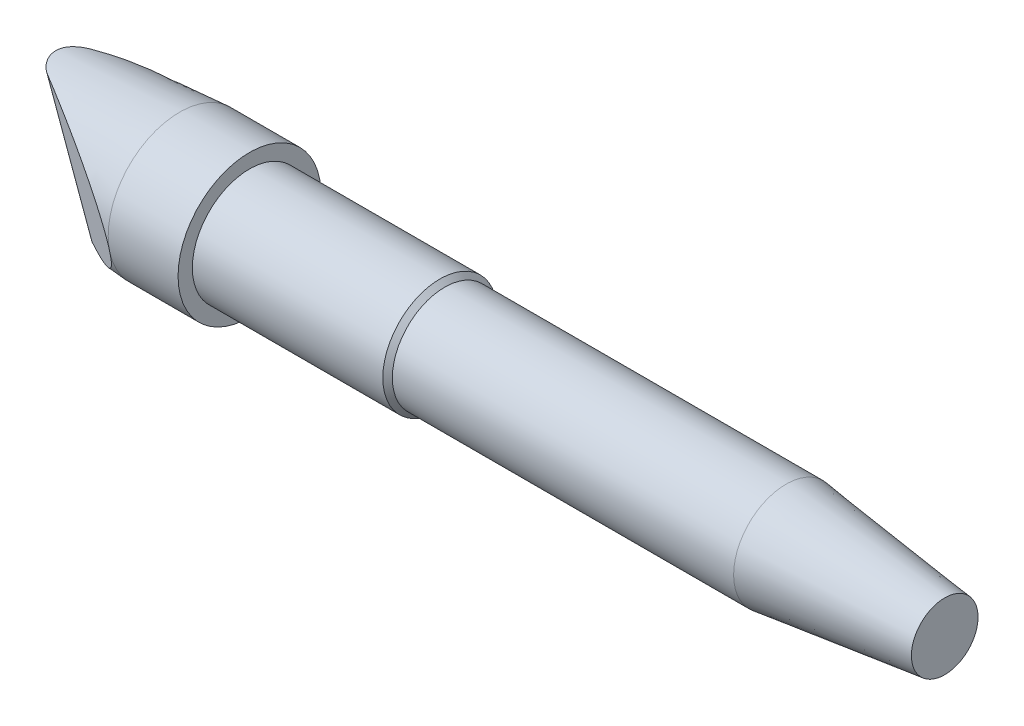
SolidWorks part; units mm, degrees
ref_plane "Plano frontal" through (0, 0, 0) normal (0, 0, 1) x (1, 0, 0)
ref_plane "Plano superior" through (0, 0, 0) normal (0, 1, 0) x (1, 0, 0)
ref_plane "Plano direito" through (0, 0, 0) normal (1, 0, 0) x (0, 0, -1)
sketch "Esboço1" plane through (0, 0, 0) normal (0, 0, 1) x (1, 0, 0)
  line L0 (0, 0) -> (29.4388, 0) construction
  line L1 (6.2, 2.25) -> (6.2, 1.8)
  line L2 (6.2, 2.25) -> (4.7, 2.25)
  line L3 (0, 2.25) -> (4.7, 2.25) construction
  line L4 (0, 2.25) -> (0, 0) construction
  line L5 (12.35, 1.65) -> (23.1, 1.65)
  line L6 (23.1, 1.65) -> (28.1, 1.05)
  line L7 (28.1, 1.05) -> (28.1, 0)
  line L8 (0, 0) -> (28.1, 0)
  line L9 (6.2, 1.8) -> (12.2, 1.8)
  line L10 (12.2, 1.8) -> (12.35, 1.65)
  line L11 (4, 2.25) -> (0, 1.9703)
  line L12 (0, 1.9703) -> (0, 0)
  line L13 (4, 2.25) -> (4.7, 2.25)
  dimension "D1" = 1.5
  dimension "D2" = 6.2
  dimension "D3" = 4.5
  dimension "D4" = 45
  dimension "D5" = 2.1
  dimension "D6" = 5
  dimension "D7" = 28.1
  dimension "D8" = 4
  dimension "D9" = 3.3
  dimension "D10" = 3.6
  dimension "D11" = 6
  dimension "D12" = 4
revolve "Revolução1" add sketch "Esboço1" angle 360 about L8
sketch "Esboço2" plane through (0, 0, 0) normal (0, 0, 1) x (1, 0, 0)
  line L0 (0, 1.9703) -> (1.4717, -2.0732)
  line L1 (0, -1.9703) -> (4, -2.25) construction
  line L2 (0, 1.9703) -> (0, -1.9703) construction
  line L3 (0, 1.9703) -> (-0.3953, 3.0565)
  line L4 (-0.9312, 3.0565) -> (-0.9312, -4.421)
  line L5 (-0.9312, -4.421) -> (2.3262, -4.421)
  line L6 (2.3262, -4.421) -> (1.4717, -2.0732)
  line L7 (-0.3953, 3.0565) -> (-0.9312, 3.0565)
  dimension "D1" = 20
ref_plane "Plano1" through (0, 2.25, 0) normal (0, 1, 0) x (-1, 0, 0)
extrude "Corte-extrusão2" cut sketch "Esboço2" against normal mid plane 10
sketch "Esboço3" plane through (3.8636, 2.25, 0) normal (0, 1, 0) x (0, 0, -1)
  line L0 (0.4619, 3.8635) -> (4.5033, -3.1364) construction
  line L1 (-4.5033, -3.1364) -> (-0.6928, 3.4636)
  line L2 (0, 3.8636) -> (0, -20.7464) construction
  line L3 (0.6928, 3.4636) -> (4.5033, -3.1364)
  line L4 (0.4619, 3.8635) -> (0, 4.6635) construction
  line L5 (0, 4.6635) -> (-0.4619, 3.8635) construction
  line L6 (-0.4619, 3.8635) -> (-4.5033, -3.1364) construction
  arc A0 (4.5033, -3.1364) -> (-4.5033, -3.1364) centre (0, 4.6635) ccw
  arc A1 (-0.6928, 3.4636) -> (0.6928, 3.4636) centre (0, 3.0636) cw
  dimension "D1" = 0.9238
  dimension "D4" = 7
  dimension "D2" = 60
  dimension "D3" = 0.8
extrude "Corte-extrusão1" cut sketch "Esboço3" along direction (0.342, -0.9397, 0) on the side against the normal blind 10
